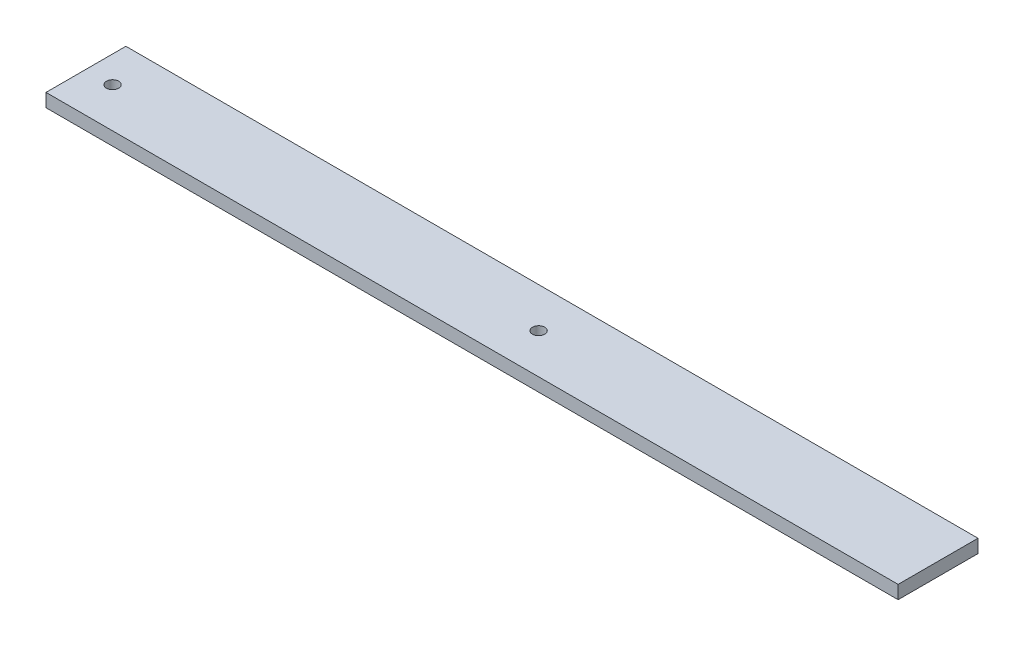
SolidWorks part; units mm, degrees
ref_plane "Front Plane" through (0, 0, 0) normal (0, 0, 1) x (1, 0, 0)
ref_plane "Top Plane" through (0, 0, 0) normal (0, 1, 0) x (1, 0, 0)
ref_plane "Right Plane" through (0, 0, 0) normal (1, 0, 0) x (0, 0, -1)
sketch "Sketch1" plane through (0, 0, 0) normal (0, 1, 0) x (1, 0, 0)
  line L1 (0, 0) -> (203.2, 0)
  line L2 (0, 0) -> (0, 19.05)
  line L3 (0, 19.05) -> (203.2, 19.05)
  line L4 (203.2, 0) -> (203.2, 19.05)
  circle A0 centre (6.35, 9.525) radius 1.4605
  circle A1 centre (107.95, 9.525) radius 1.4605
  dimension "D3" = 2.921
  dimension "D6" = 2.921
  dimension "D8" = 107.95
  dimension "D1" = 203.2
  dimension "D2" = 19.05
  dimension "D4" = 6.35
  dimension "D5" = 9.525
  dimension "D7" = 9.525
extrude "Boss-Extrude1" add sketch "Sketch1" along normal blind 3.175
